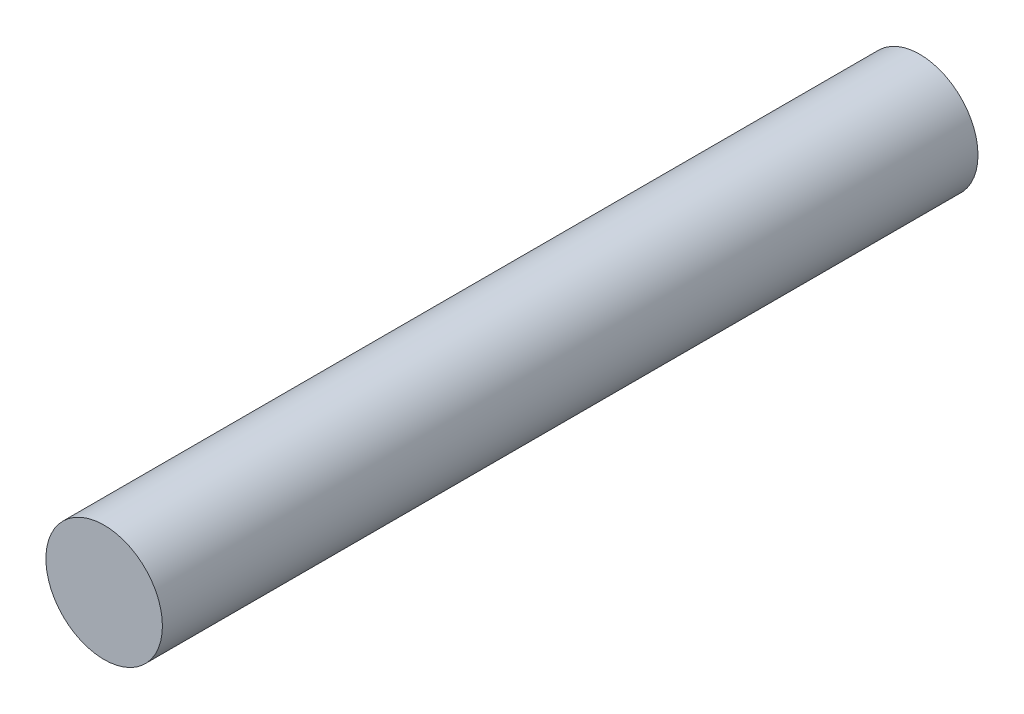
SolidWorks part; units mm, degrees
ref_plane "Front Plane" through (0, 0, 0) normal (0, 0, 1) x (1, 0, 0)
ref_plane "Top Plane" through (0, 0, 0) normal (0, 1, 0) x (1, 0, 0)
ref_plane "Right Plane" through (0, 0, 0) normal (1, 0, 0) x (0, 0, -1)
sketch "Sketch1" plane through (0, 0, 0) normal (0, 0, 1) x (1, 0, 0)
  circle A0 centre (-736.6, -12.7) radius 6.35
extrude "Boss-Extrude1" add sketch "Sketch1" along normal blind 88.9
